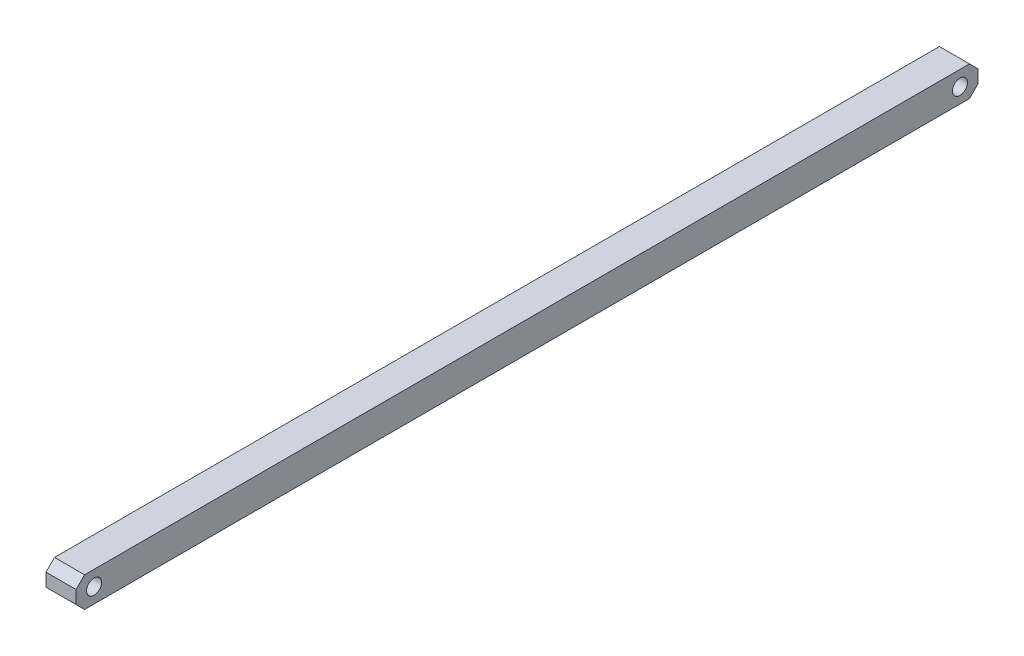
SolidWorks part; units mm, degrees
ref_plane "正面" through (0, 0, 0) normal (0, 0, 1) x (1, 0, 0)
ref_plane "平面" through (0, 0, 0) normal (0, 1, 0) x (1, 0, 0)
ref_plane "右側面" through (0, 0, 0) normal (1, 0, 0) x (0, 0, -1)
sketch "ｽｹｯﾁ1" plane through (0, 0, 0) normal (0, 0, 1) x (1, 0, 0)
  line L1 (0, 0) -> (10, 0)
  line L2 (0, 0) -> (0, -10)
  line L3 (0, -10) -> (10, -10)
  line L4 (10, 0) -> (10, -10)
  dimension "D1" = 10
  dimension "D2" = 10
extrude "ﾎﾞｽ - 押し出し1" add sketch "ｽｹｯﾁ1" along normal blind 300
sketch "ｽｹｯﾁ2" plane through (10, 0, 0) normal (1, 0, 0) x (0, 0, -1)
  line L0 (-2.8284, 0) -> (0, -2.8284)
  line L1 (-300, 0) -> (0, 0) construction
  line L2 (0, -5) -> (-6, -5) construction
  line L3 (0, -10) -> (0, 0) construction
  line L4 (0, -7.1716) -> (-2.8284, -10)
  line L5 (-300, -10) -> (0, -10) construction
  line L6 (-2.8284, -10) -> (0, -10)
  line L7 (0, -10) -> (0, -7.1716)
  line L8 (0, -2.8284) -> (0, 0)
  line L9 (0, 0) -> (-2.8284, 0)
  line L10 (-2.8284, -10) -> (-2.8284, 0) construction
  line L11 (-150, 0) -> (-150, -10) construction
  line L12 (-297.1716, -10) -> (-297.1716, 0) construction
  line L13 (-300, -5) -> (-294, -5) construction
  line L14 (-300, 0) -> (-297.1716, 0)
  line L15 (-300, -2.8284) -> (-300, 0)
  line L16 (-300, -10) -> (-300, -7.1716)
  line L17 (-297.1716, -10) -> (-300, -10)
  line L18 (-300, -7.1716) -> (-297.1716, -10)
  line L19 (-297.1716, 0) -> (-300, -2.8284)
  circle A0 centre (-6, -5) radius 2.5
  circle A1 centre (-294, -5) radius 2.5
  dimension "D2" = 5
  dimension "D3" = 6
  dimension "D1" = 4
extrude "ｶｯﾄ - 押し出し1" cut sketch "ｽｹｯﾁ2" against normal through all
